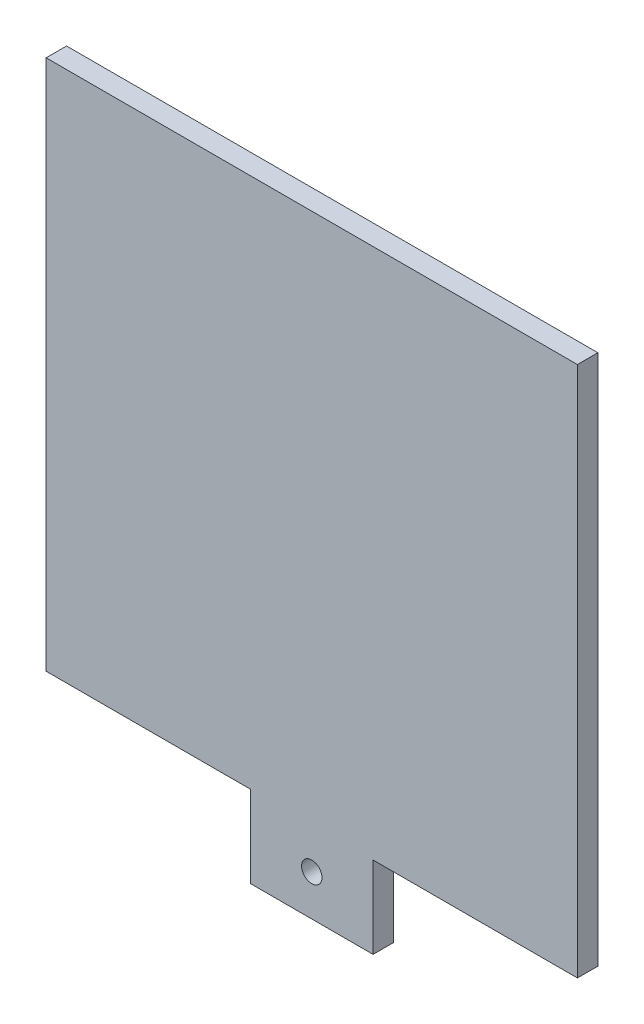
SolidWorks part; units mm, degrees
ref_plane "Přední rovina" through (0, 0, 0) normal (0, 0, 1) x (1, 0, 0)
ref_plane "Horní rovina" through (0, 0, 0) normal (0, 1, 0) x (1, 0, 0)
ref_plane "Pravá rovina" through (0, 0, 0) normal (1, 0, 0) x (0, 0, -1)
sketch "Skica1" plane through (0, 0, 0) normal (0, 0, 1) x (1, 0, 0)
  line L0 (-15, -85) -> (-15, -65)
  line L1 (-65, 65) -> (65, 65)
  line L2 (-65, 65) -> (-65, -65)
  line L3 (-65, -65) -> (-15, -65)
  line L4 (65, 65) -> (65, -65)
  line L5 (-65, 65) -> (65, -65) construction
  line L6 (-65, -65) -> (65, 65) construction
  line L7 (-15, -85) -> (15, -85)
  line L9 (15, -85) -> (15, -65)
  line L10 (-15, -85) -> (15, -65) construction
  line L11 (-15, -65) -> (15, -85) construction
  line L12 (15, -65) -> (65, -65)
  point P0 (0, 0)
  point P6 (0, 0)
  point P7 (0, -75)
  dimension "D1" = 130
  dimension "D2" = 130
  dimension "D3" = 20
  dimension "D4" = 30
extrude "Přidat vysunutím1" add sketch "Skica1" along normal blind 5
sketch "Skica2" plane through (0, 0, 0) normal (0, 0, -1) x (-1, 0, 0)
  line L0 (15, -65) -> (15, -85) construction
  line L1 (15, -85) -> (-15, -85) construction
  circle A0 centre (0, -75) radius 2.5
  dimension "D1" = 5
  dimension "D2" = 15
  dimension "10" = 10
extrude "Odebrat vysunutím1" cut sketch "Skica2" against normal blind 5
